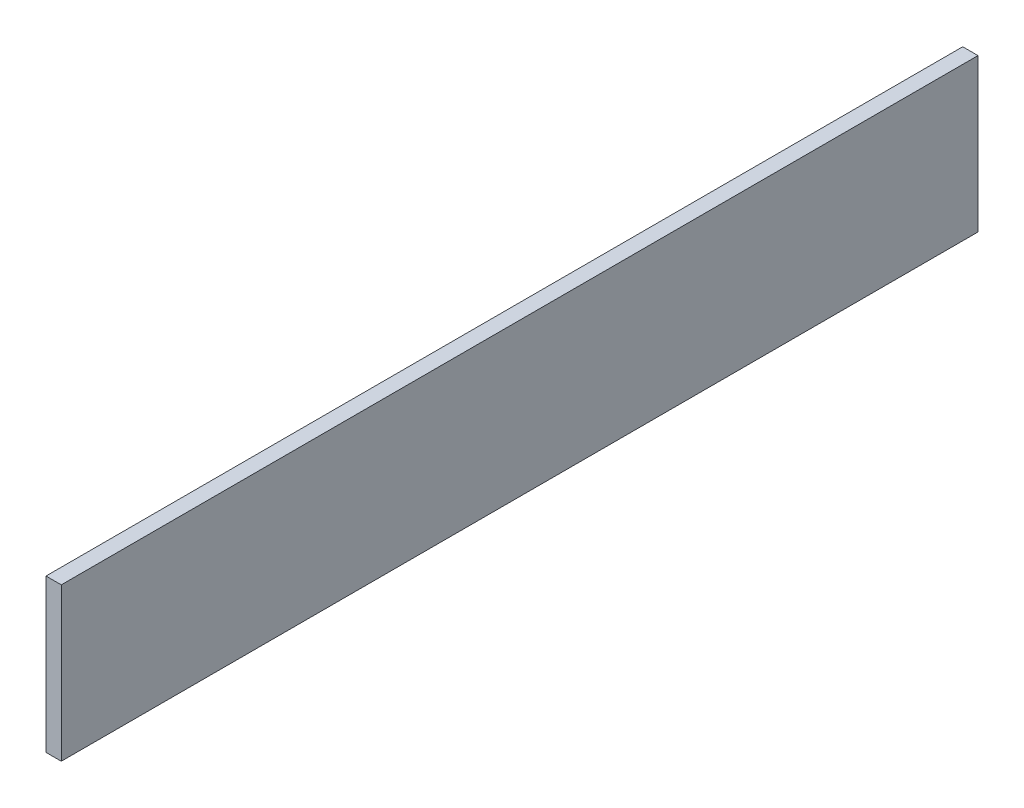
SolidWorks part; units mm, degrees
ref_plane "Front Plane" through (0, 0, 0) normal (0, 0, 1) x (1, 0, 0)
ref_plane "Top Plane" through (0, 0, 0) normal (0, 1, 0) x (1, 0, 0)
ref_plane "Right Plane" through (0, 0, 0) normal (1, 0, 0) x (0, 0, -1)
sketch "Sketch1" plane through (0, 0, 0) normal (0, 1, 0) x (1, 0, 0)
  line L1 (0, 0) -> (1, 0)
  line L2 (0, 0) -> (0, 60)
  line L3 (0, 60) -> (1, 60)
  line L4 (1, 0) -> (1, 60)
  dimension "D1" = 1
  dimension "D2" = 60
extrude "Boss-Extrude1" add sketch "Sketch1" along normal blind 10
